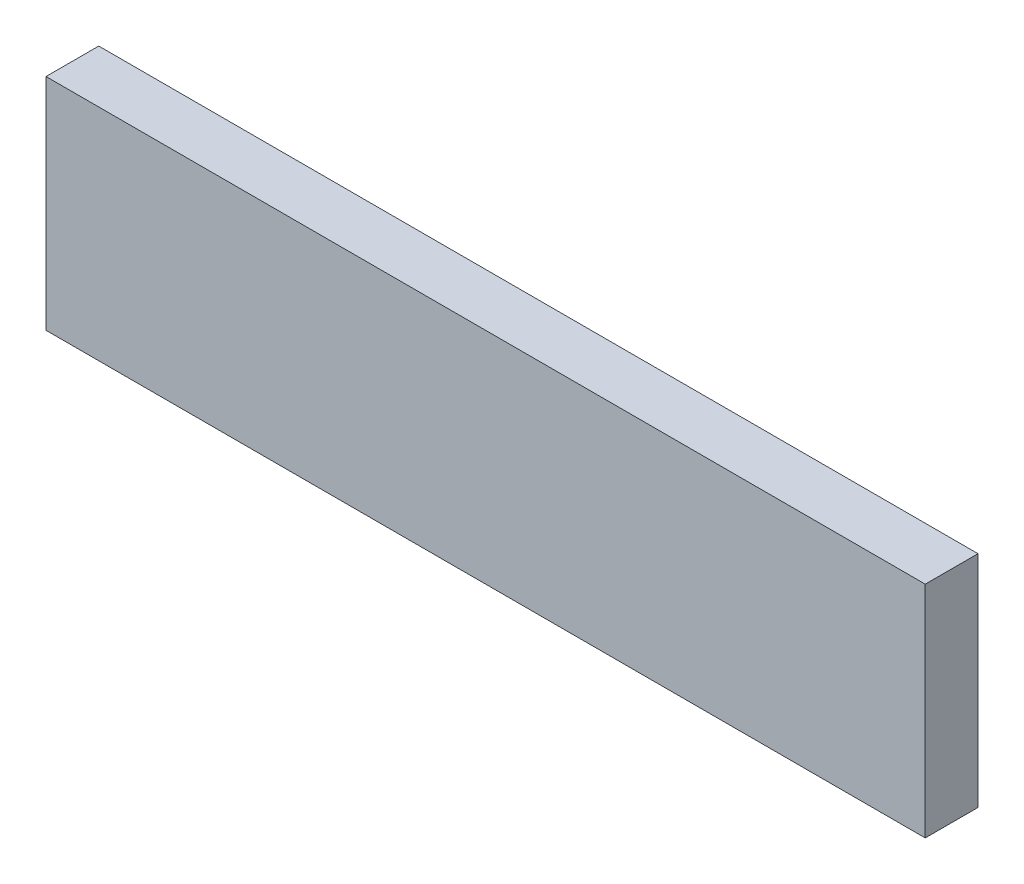
SolidWorks part; units mm, degrees
material "Acrylic (Medium-high impact)"
ref_plane "Front Plane" through (0, 0, 0) normal (0, 0, 1) x (1, 0, 0)
ref_plane "Top Plane" through (0, 0, 0) normal (0, 1, 0) x (1, 0, 0)
ref_plane "Right Plane" through (0, 0, 0) normal (1, 0, 0) x (0, 0, -1)
sketch "Sketch1" plane through (0, 0, 0) normal (0, 0, 1) x (1, 0, 0)
  line L1 (-142.8571, 43.0195) -> (-42.8571, 43.0195)
  line L2 (-142.8571, 43.0195) -> (-142.8571, 18.0195)
  line L3 (-142.8571, 18.0195) -> (-42.8571, 18.0195)
  line L4 (-42.8571, 43.0195) -> (-42.8571, 18.0195)
  dimension "D1" = 25
  dimension "D2" = 100
extrude "Boss-Extrude1" add sketch "Sketch1" along normal blind 6
